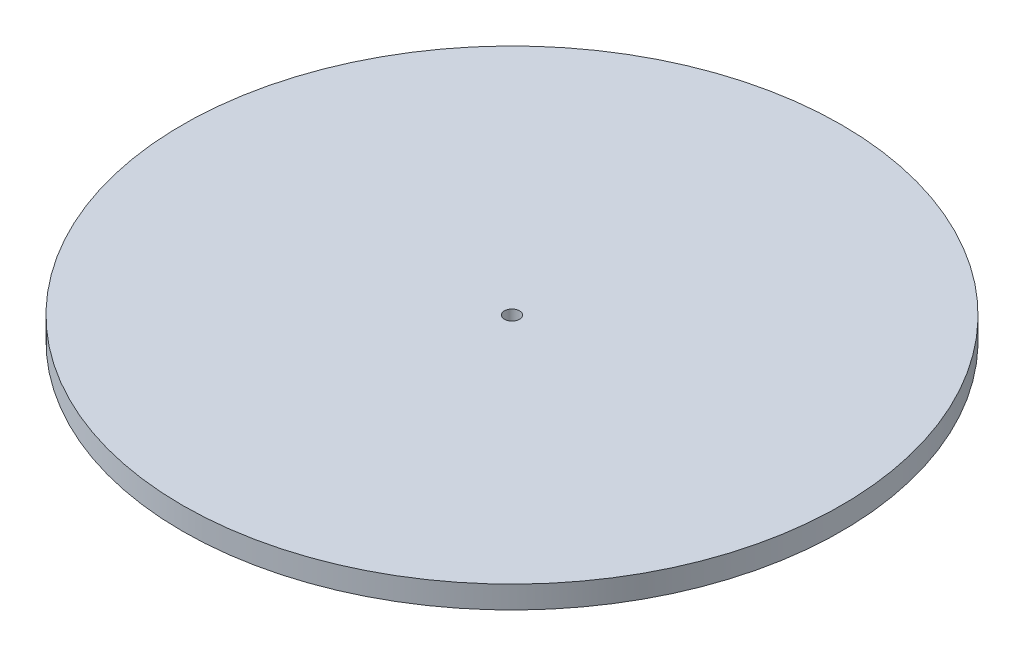
SolidWorks part; units mm, degrees
ref_plane "Front Plane" through (0, 0, 0) normal (0, 0, 1) x (1, 0, 0)
ref_plane "Top Plane" through (0, 0, 0) normal (0, 1, 0) x (1, 0, 0)
ref_plane "Right Plane" through (0, 0, 0) normal (1, 0, 0) x (0, 0, -1)
sketch "BasePlate" plane through (0, 0, 0) normal (0, 1, 0) x (1, 0, 0)
  circle A0 centre (0, 0) radius 279.9456
  dimension "D1" = 559.8912
extrude "Boss-Extrude1" add sketch "BasePlate" along normal blind 19.05
sketch "CenterHole" plane through (0, 19.05, 0) normal (0, 1, 0) x (1, 0, 0)
  circle A0 centre (0, 0) radius 6.35
  dimension "D1" = 12.7
extrude "Cut-Extrude1" cut sketch "CenterHole" against normal up to next
